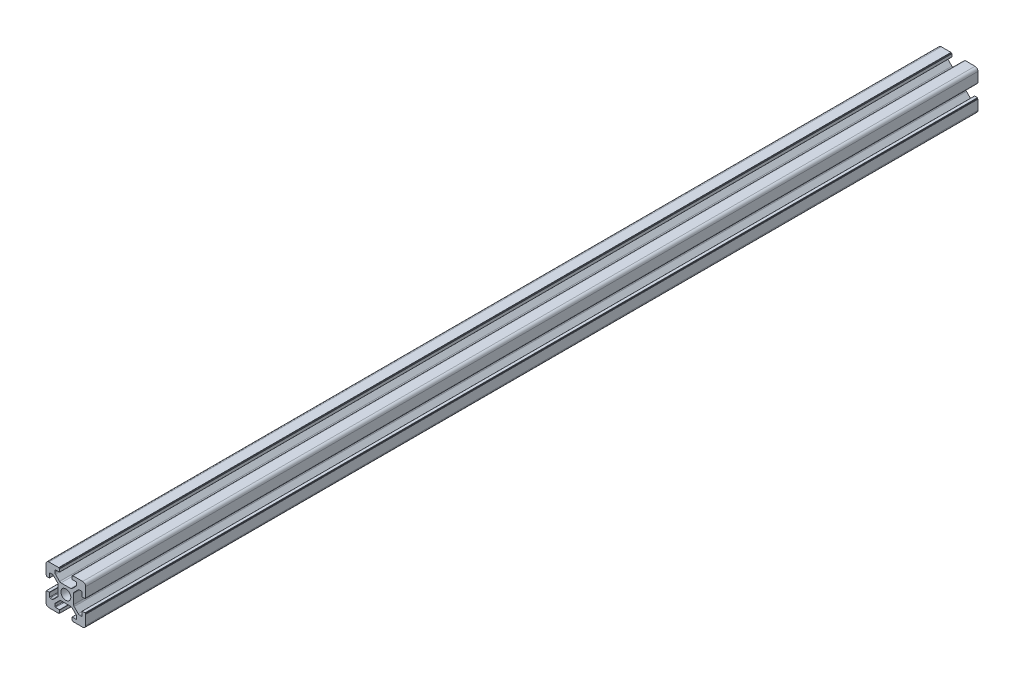
SolidWorks part; units mm, degrees
material "6063-T5"
ref_plane "前视基准面" through (0, 0, 0) normal (0, 0, 1) x (1, 0, 0)
ref_plane "上视基准面" through (0, 0, 0) normal (0, 1, 0) x (1, 0, 0)
ref_plane "右视基准面" through (0, 0, 0) normal (1, 0, 0) x (0, 0, -1)
sketch "草图1" plane through (0, 0, 0) normal (0, 0, 1) x (1, 0, 0)
  line L0 (-1.4389, 10) -> (24.3741, 10) construction
  line L1 (20, 13.6) -> (20, 20)
  line L2 (0, 0) -> (0, 6.4)
  line L3 (0, 20) -> (6.4, 20)
  line L4 (20, 0) -> (20, 6.4)
  line L5 (10, 21.5388) -> (10, -2.4017) construction
  line L6 (6.9, 18.3) -> (6.9, 19.7)
  line L7 (6.8, 18.2) -> (4.8, 18.2)
  line L8 (4.5, 17.9) -> (4.5, 16.9749)
  line L9 (4.7929, 16.2678) -> (6.8678, 14.1929)
  line L10 (7.5749, 13.9) -> (12.4251, 13.9)
  line L11 (6.8, 19.8) -> (6.4, 19.8)
  line L12 (6.4, 19.8) -> (6.4, 20)
  line L13 (0, 13.6) -> (0.2, 13.6)
  line L14 (0.2, 13.6) -> (0.2, 13.2)
  line L15 (0.3, 13.1) -> (1.7, 13.1)
  line L16 (1.8, 13.2) -> (1.8, 15.2)
  line L17 (2.1, 15.5) -> (3.0251, 15.5)
  line L18 (3.7322, 15.2071) -> (5.8071, 13.1322)
  line L19 (6.1, 12.4251) -> (6.1, 7.5749)
  line L20 (13.6, 19.8) -> (13.6, 20)
  line L21 (13.2, 19.8) -> (13.6, 19.8)
  line L22 (13.1, 18.3) -> (13.1, 19.7)
  line L23 (13.2, 18.2) -> (15.2, 18.2)
  line L24 (15.5, 17.9) -> (15.5, 16.9749)
  line L25 (15.2071, 16.2678) -> (13.1322, 14.1929)
  line L26 (0, 6.4) -> (0.2, 6.4)
  line L27 (0.2, 6.4) -> (0.2, 6.8)
  line L28 (0.3, 6.9) -> (1.7, 6.9)
  line L29 (1.8, 6.8) -> (1.8, 4.8)
  line L30 (2.1, 4.5) -> (3.0251, 4.5)
  line L31 (3.7322, 4.7929) -> (5.8071, 6.8678)
  line L32 (13.6, 20) -> (20, 20)
  line L33 (0, 13.6) -> (0, 20)
  line L34 (13.6, 0.2) -> (13.6, 0)
  line L35 (13.2, 0.2) -> (13.6, 0.2)
  line L36 (13.1, 1.7) -> (13.1, 0.3)
  line L37 (13.2, 1.8) -> (15.2, 1.8)
  line L38 (15.5, 2.1) -> (15.5, 3.0251)
  line L39 (15.2071, 3.7322) -> (13.1322, 5.8071)
  line L40 (4.5, 2.1) -> (4.5, 3.0251)
  line L41 (6.8, 1.8) -> (4.8, 1.8)
  line L42 (6.4, 0.2) -> (6.4, 0)
  line L43 (6.8, 0.2) -> (6.4, 0.2)
  line L44 (6.9, 1.7) -> (6.9, 0.3)
  line L45 (4.7929, 3.7322) -> (6.8678, 5.8071)
  line L46 (7.5749, 6.1) -> (12.4251, 6.1)
  line L47 (20, 6.4) -> (19.8, 6.4)
  line L48 (19.8, 6.4) -> (19.8, 6.8)
  line L49 (19.7, 6.9) -> (18.3, 6.9)
  line L50 (18.2, 6.8) -> (18.2, 4.8)
  line L51 (17.9, 4.5) -> (16.9749, 4.5)
  line L52 (16.2678, 4.7929) -> (14.1929, 6.8678)
  line L53 (13.9, 12.4251) -> (13.9, 7.5749)
  line L54 (16.2678, 15.2071) -> (14.1929, 13.1322)
  line L55 (17.9, 15.5) -> (16.9749, 15.5)
  line L56 (18.2, 13.2) -> (18.2, 15.2)
  line L57 (19.7, 13.1) -> (18.3, 13.1)
  line L58 (19.8, 13.6) -> (19.8, 13.2)
  line L59 (20, 13.6) -> (19.8, 13.6)
  line L60 (0, 0) -> (6.4, 0)
  line L61 (13.6, 0) -> (20, 0)
  arc A0 (6.1, 12.4251) -> (5.8071, 13.1322) centre (5.1, 12.4251) ccw
  arc A1 (7.5749, 13.9) -> (6.8678, 14.1929) centre (7.5749, 14.9) cw
  arc A2 (4.5, 16.9749) -> (4.7929, 16.2678) centre (5.5, 16.9749) ccw
  arc A3 (3.7322, 15.2071) -> (3.0251, 15.5) centre (3.0251, 14.5) ccw
  arc A4 (4.5, 17.9) -> (4.8, 18.2) centre (4.8, 17.9) cw
  arc A5 (1.8, 15.2) -> (2.1, 15.5) centre (2.1, 15.2) cw
  arc A6 (0.3, 13.1) -> (0.2, 13.2) centre (0.3, 13.2) cw
  arc A7 (6.9, 19.7) -> (6.8, 19.8) centre (6.8, 19.7) ccw
  arc A8 (1.7, 13.1) -> (1.8, 13.2) centre (1.7, 13.2) ccw
  arc A9 (6.9, 18.3) -> (6.8, 18.2) centre (6.8, 18.3) cw
  arc A10 (13.1, 19.7) -> (13.2, 19.8) centre (13.2, 19.7) cw
  arc A11 (13.1, 18.3) -> (13.2, 18.2) centre (13.2, 18.3) ccw
  arc A12 (15.5, 17.9) -> (15.2, 18.2) centre (15.2, 17.9) ccw
  arc A13 (15.5, 16.9749) -> (15.2071, 16.2678) centre (14.5, 16.9749) cw
  arc A14 (12.4251, 13.9) -> (13.1322, 14.1929) centre (12.4251, 14.9) ccw
  arc A15 (0.3, 6.9) -> (0.2, 6.8) centre (0.3, 6.8) ccw
  arc A16 (1.7, 6.9) -> (1.8, 6.8) centre (1.7, 6.8) cw
  arc A17 (1.8, 4.8) -> (2.1, 4.5) centre (2.1, 4.8) ccw
  arc A18 (3.7322, 4.7929) -> (3.0251, 4.5) centre (3.0251, 5.5) cw
  arc A19 (6.1, 7.5749) -> (5.8071, 6.8678) centre (5.1, 7.5749) cw
  arc A20 (13.1, 0.3) -> (13.2, 0.2) centre (13.2, 0.3) ccw
  arc A21 (13.1, 1.7) -> (13.2, 1.8) centre (13.2, 1.7) cw
  arc A22 (15.5, 2.1) -> (15.2, 1.8) centre (15.2, 2.1) cw
  arc A23 (15.5, 3.0251) -> (15.2071, 3.7322) centre (14.5, 3.0251) ccw
  arc A24 (12.4251, 6.1) -> (13.1322, 5.8071) centre (12.4251, 5.1) cw
  arc A25 (4.5, 2.1) -> (4.8, 1.8) centre (4.8, 2.1) ccw
  arc A26 (6.9, 0.3) -> (6.8, 0.2) centre (6.8, 0.3) cw
  arc A27 (6.9, 1.7) -> (6.8, 1.8) centre (6.8, 1.7) ccw
  arc A28 (4.5, 3.0251) -> (4.7929, 3.7322) centre (5.5, 3.0251) cw
  arc A29 (7.5749, 6.1) -> (6.8678, 5.8071) centre (7.5749, 5.1) ccw
  arc A30 (19.7, 6.9) -> (19.8, 6.8) centre (19.7, 6.8) cw
  arc A31 (18.3, 6.9) -> (18.2, 6.8) centre (18.3, 6.8) ccw
  arc A32 (18.2, 4.8) -> (17.9, 4.5) centre (17.9, 4.8) cw
  arc A33 (16.2678, 4.7929) -> (16.9749, 4.5) centre (16.9749, 5.5) ccw
  arc A34 (13.9, 7.5749) -> (14.1929, 6.8678) centre (14.9, 7.5749) ccw
  arc A35 (13.9, 12.4251) -> (14.1929, 13.1322) centre (14.9, 12.4251) cw
  arc A36 (16.2678, 15.2071) -> (16.9749, 15.5) centre (16.9749, 14.5) cw
  arc A37 (18.2, 15.2) -> (17.9, 15.5) centre (17.9, 15.2) ccw
  arc A38 (18.3, 13.1) -> (18.2, 13.2) centre (18.3, 13.2) cw
  arc A39 (19.7, 13.1) -> (19.8, 13.2) centre (19.7, 13.2) ccw
  circle A40 centre (10, 10) radius 2.5
  point P39 (0.2, 13.1)
  point P42 (6.9, 19.8)
  point P45 (1.8, 13.1)
  point P48 (6.9, 18.2)
  point P66 (10, 13.9)
  point P83 (6.1, 10)
  dimension "D19" = 1
  dimension "D20" = 1
  dimension "D21" = 0.3
  dimension "D22" = 0.1
  dimension "D23" = 5
  dimension "D1" = 20
  dimension "D2" = 20
  dimension "D3" = 10
  dimension "D4" = 10
  dimension "D5" = 1.8
  dimension "D6" = 0.5
  dimension "D7" = 1.6
  dimension "D8" = 3.1
  dimension "D9" = 6.1
  dimension "D10" = 5.5
  dimension "D11" = 3.1
  dimension "D12" = 6.1
  dimension "D13" = 5.5
  dimension "D14" = 1.8
  dimension "D15" = 0.5
  dimension "D16" = 1.5
  dimension "D17" = 45
  dimension "D18" = 1.6
extrude "凸台-拉伸1" add sketch "草图1" along normal blind 450
fillet "圆角1" radius 1.5 4 edges at (20, 0, 225) (0, 0, 225) (0, 20, 225) (20, 20, 225)
